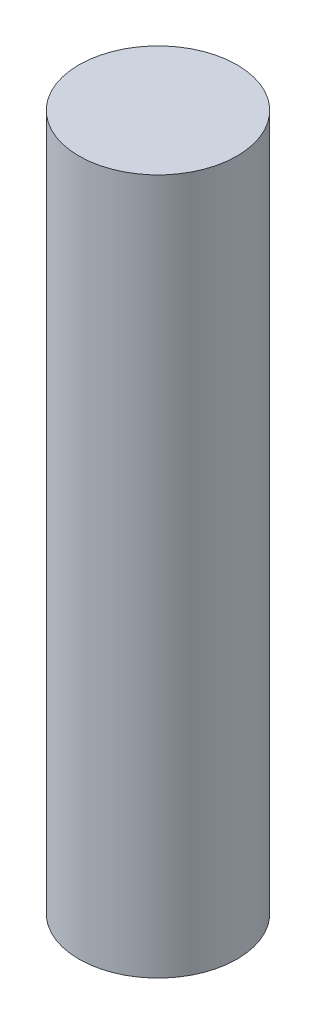
SolidWorks part; units mm, degrees
ref_plane "Front Plane" through (0, 0, 0) normal (0, 0, 1) x (1, 0, 0)
ref_plane "Top Plane" through (0, 0, 0) normal (0, 1, 0) x (1, 0, 0)
ref_plane "Right Plane" through (0, 0, 0) normal (1, 0, 0) x (0, 0, -1)
sketch "Sketch1" plane through (0, 0, 0) normal (0, 1, 0) x (1, 0, 0)
  circle A0 centre (0, 0) radius 3.9688
  dimension "D1" = 7.9375
extrude "Boss-Extrude1" add sketch "Sketch1" along normal blind 34.925
cosmetic thread "Cosmetic Thread1" parameters "D1"=19.05, "D2"=6.2586
hole_wizard "#10-32 Tapped Hole1" positions "Sketch3" profile "Sketch4" tap size "#10-32" standard "ANSI Inch"
sketch "Sketch3" plane through (0, 0, 0) normal (0, -1, 0) x (-1, 0, 0)
  point P0 (0, 0)
sketch "Sketch4" plane through (0, 0, 0) normal (1, 0, 0) x (0, 0, -1)
  line L0 (0, 0) -> (0, 8.8333)
  line L1 (0, 8.8333) -> (2.0193, 7.62)
  line L2 (2.0193, 7.62) -> (2.0193, 0)
  line L5 (2.0193, 0) -> (0, 0)
  line L10 (0, 8.8333) -> (-2.0193, 7.62) construction
  line L11 (0, -6.35) -> (0, 107.95) construction
  dimension "Tap Drill Dia." = 4.0386
  dimension "Tap Drill Depth" = 7.62
  dimension "Drill Angle" = 118
cosmetic thread "Hole Thread1" parameters "D1"=7.62, "D2"=4.826
